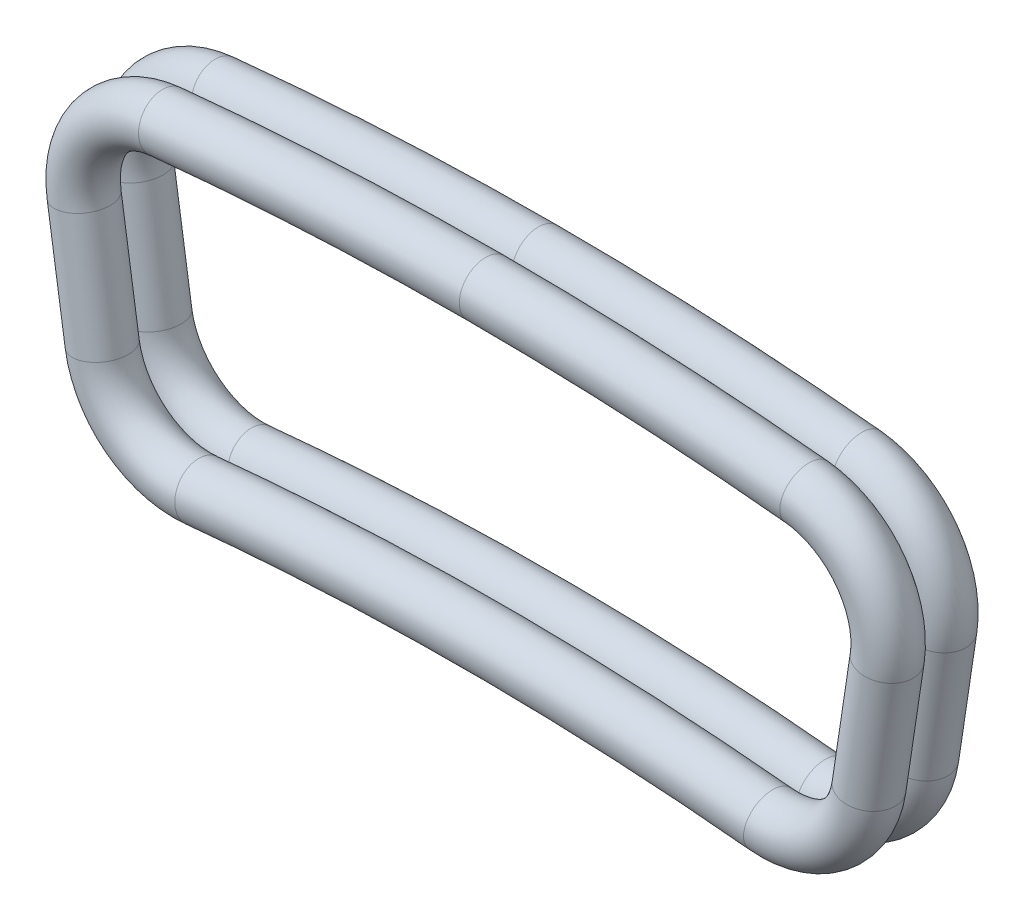
SolidWorks part; units mm, degrees
material "Copper"
ref_plane "Front Plane" through (0, 0, 0) normal (0, 0, 1) x (1, 0, 0)
ref_plane "Top Plane" through (0, 0, 0) normal (0, 1, 0) x (1, 0, 0)
ref_plane "Right Plane" through (0, 0, 0) normal (1, 0, 0) x (0, 0, -1)
sketch "Sketch1" plane through (0, 0, 0) normal (0, 0, 1) x (1, 0, 0)
  line L0 (11.8453, 90.7593) -> (12.404, 94.466)
  line L1 (-12.404, 94.466) -> (-11.8453, 90.7593)
  line L2 (11.0404, 90.8806) -> (11.5991, 94.5874)
  line L3 (-11.5991, 94.5874) -> (-11.0404, 90.8806)
  line L4 (11.0404, 90.8806) -> (11.5991, 94.5874) construction
  line L5 (-11.5991, 94.5874) -> (-11.0404, 90.8806) construction
  arc A0 (12.404, 94.466) -> (9.9053, 97.6851) centre (9.6214, 94.8854) ccw
  arc A1 (9.9053, 97.6851) -> (-9.9053, 97.6851) centre (0, 0) ccw
  arc A2 (-9.9053, 97.6851) -> (-12.404, 94.466) centre (-9.6214, 94.8854) ccw
  arc A3 (-11.8453, 90.7593) -> (-8.7844, 88.3785) centre (-9.0627, 91.1787) ccw
  arc A4 (8.7844, 88.3785) -> (-8.7844, 88.3785) centre (0, 0) ccw
  arc A5 (8.7844, 88.3785) -> (11.8453, 90.7593) centre (9.0627, 91.1787) ccw
  arc A6 (11.5991, 94.5874) -> (9.8232, 96.8752) centre (9.6214, 94.8854) ccw
  arc A7 (9.8232, 96.8752) -> (-9.8232, 96.8752) centre (0, 0) ccw
  arc A8 (-9.8232, 96.8752) -> (-11.5991, 94.5874) centre (-9.6214, 94.8854) ccw
  arc A9 (-11.0404, 90.8806) -> (-8.8649, 89.1885) centre (-9.0627, 91.1787) ccw
  arc A10 (8.8649, 89.1885) -> (-8.8649, 89.1885) centre (0, 0) ccw
  arc A11 (8.8649, 89.1885) -> (11.0404, 90.8806) centre (9.0627, 91.1787) ccw
  arc A12 (11.5991, 94.5874) -> (9.8232, 96.8752) centre (9.6214, 94.8854) ccw construction
  arc A13 (9.8232, 96.8752) -> (-9.8232, 96.8752) centre (0, 0) ccw construction
  arc A14 (-9.8232, 96.8752) -> (-11.5991, 94.5874) centre (-9.6214, 94.8854) ccw construction
  arc A15 (-11.0404, 90.8806) -> (-8.8649, 89.1885) centre (-9.0627, 91.1787) ccw construction
  arc A16 (8.8649, 89.1885) -> (-8.8649, 89.1885) centre (0, 0) ccw construction
  arc A17 (8.8649, 89.1885) -> (11.0404, 90.8806) centre (9.0627, 91.1787) ccw construction
  dimension "D1" = 0
  dimension "D2" = 0.814
ref_plane "Plane1" through (0, 0, -3.186) normal (0, 0, 1) x (1, 0, 0)
sketch "Sketch3" plane through (0, 0, -3.186) normal (0, 0, 1) x (1, 0, 0)
  line L0 (11.8453, 90.7593) -> (12.404, 94.466) construction
  line L1 (-12.404, 94.466) -> (-11.8453, 90.7593) construction
  line L2 (11.8453, 90.7593) -> (12.404, 94.466)
  line L3 (-12.404, 94.466) -> (-11.8453, 90.7593)
  arc A0 (12.404, 94.466) -> (9.9053, 97.6851) centre (9.6214, 94.8854) ccw construction
  arc A1 (8.7844, 88.3785) -> (11.8453, 90.7593) centre (9.0627, 91.1787) ccw construction
  arc A2 (8.7844, 88.3785) -> (-8.7844, 88.3785) centre (0, 0) ccw construction
  arc A3 (-11.8453, 90.7593) -> (-8.7844, 88.3785) centre (-9.0627, 91.1787) ccw construction
  arc A4 (-9.9053, 97.6851) -> (-12.404, 94.466) centre (-9.6214, 94.8854) ccw construction
  arc A5 (9.9053, 97.6851) -> (-9.9053, 97.6851) centre (0, 0) ccw construction
  arc A6 (12.404, 94.466) -> (9.9053, 97.6851) centre (9.6214, 94.8854) ccw
  arc A7 (8.7844, 88.3785) -> (11.8453, 90.7593) centre (9.0627, 91.1787) ccw
  arc A8 (8.7844, 88.3785) -> (-8.7844, 88.3785) centre (0, 0) ccw
  arc A9 (-11.8453, 90.7593) -> (-8.7844, 88.3785) centre (-9.0627, 91.1787) ccw
  arc A10 (-9.9053, 97.6851) -> (-12.404, 94.466) centre (-9.6214, 94.8854) ccw
  arc A11 (9.9053, 97.6851) -> (-9.9053, 97.6851) centre (0, 0) ccw
sketch "Sketch4" plane through (0, 0, 0) normal (1, 0, 0) x (0, 0, -1)
  circle A0 centre (3.186, 98.186) radius 0.814
  dimension "D1" = 1.628
sweep "Sweep2" add profiles "Sketch4" path "Sketch3"
pattern_linear "LPattern1" count 2 spacing 1.628 along (0, 0, 1) of bodies 102
